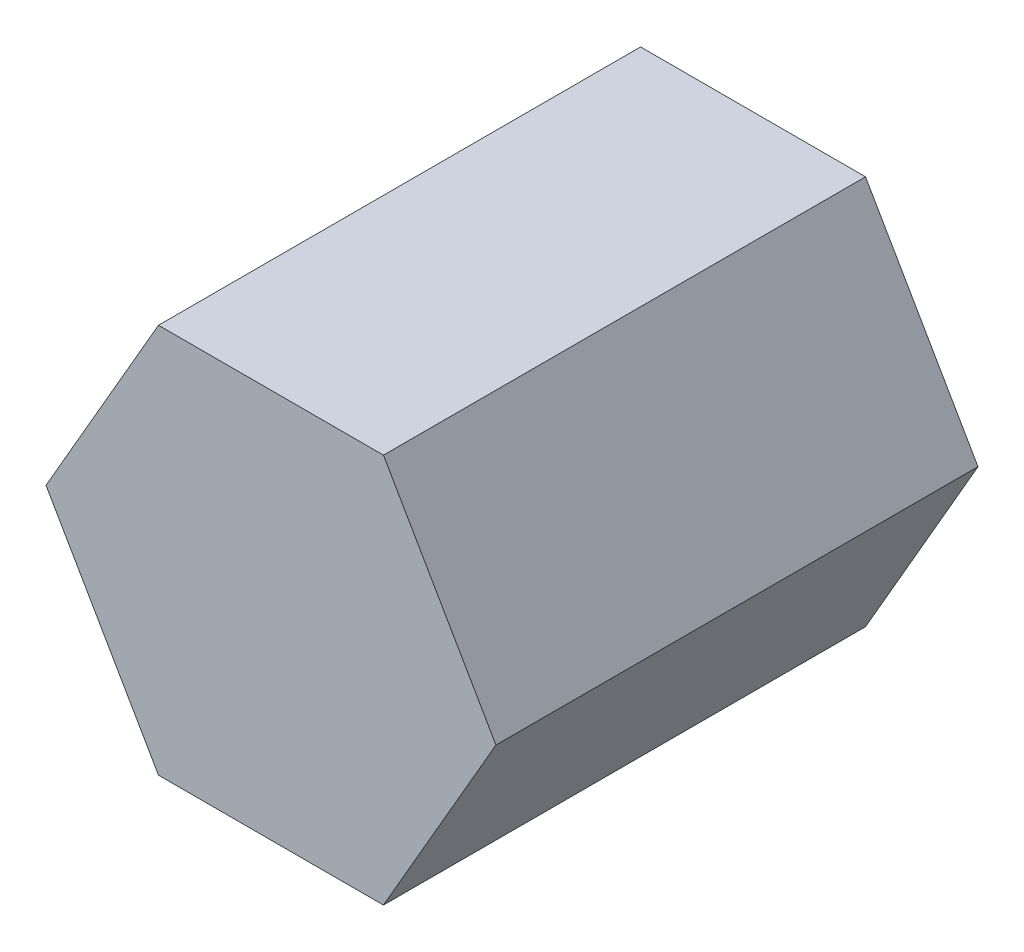
SolidWorks part; units mm, degrees
ref_plane "Front Plane" through (0, 0, 0) normal (0, 0, 1) x (1, 0, 0)
ref_plane "Top Plane" through (0, 0, 0) normal (0, 1, 0) x (1, 0, 0)
ref_plane "Right Plane" through (0, 0, 0) normal (1, 0, 0) x (0, 0, -1)
sketch "Sketch1" plane through (0, 0, 0) normal (0, 0, 1) x (1, 0, 0)
  line L0 (28, 0) -> (14, 24.2487)
  line L1 (14, 24.2487) -> (-14, 24.2487)
  line L2 (-14, 24.2487) -> (-28, 0)
  line L3 (-28, 0) -> (-14, -24.2487)
  line L4 (-14, -24.2487) -> (14, -24.2487)
  line L5 (14, -24.2487) -> (28, 0)
extrude "Prism" add sketch "Sketch1" along normal blind 60
